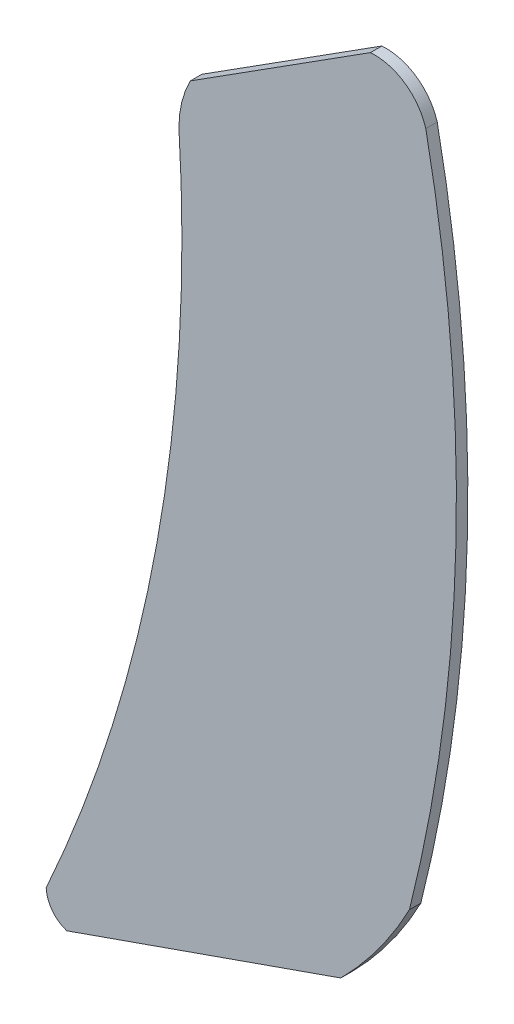
SolidWorks part; units mm, degrees
ref_plane "Спереди" through (0, 0, 0) normal (0, 0, 1) x (1, 0, 0)
ref_plane "Сверху" through (0, 0, 0) normal (0, 1, 0) x (1, 0, 0)
ref_plane "Справа" through (0, 0, 0) normal (1, 0, 0) x (0, 0, -1)
sketch "Эскиз1" plane through (0, 0, 0) normal (0, 0, 1) x (1, 0, 0)
  line L0 (79.6816, 239.4253) -> (32.4296, 209.3712)
  line L1 (71.9106, 25.2302) -> (0, 0)
  arc A0 (79.6816, 239.4253) -> (94.2106, 229.4253) centre (80.7814, 225.4686) cw
  arc A1 (94.2106, 229.4253) -> (89.9106, 49.7302) centre (-303.5993, 149.0457) cw
  arc A2 (89.9106, 49.7302) -> (71.9106, 25.2302) centre (-0.381, 97.2047) cw
  arc A3 (0, 0) -> (-5.4, 7.1) centre (2.349, 7.3901) cw
  arc A4 (32.4296, 209.3712) -> (29.4296, 197.1712) centre (55.3947, 197.2552) ccw
  arc A5 (29.4296, 197.1712) -> (-5.4, 7.1) centre (-369.7838, 172.0983) cw
  arc A6 (32.4296, 209.3712) -> (-3.3, 2.0778) centre (-302.3977, 160.357) cw
  arc A7 (79.6816, 239.4253) -> (71.9106, 25.2302) centre (-332.2163, 147.1305) cw
  point P17 (0, 0)
  point P18 (0, 0)
  point P19 (0, 0)
  point P20 (0, 0)
  point P21 (0, 0)
  point P22 (0, 0)
  point P23 (0, 0)
  point P24 (0, 0)
  dimension "D2" = 14
  dimension "D3" = 405.8492
  dimension "D4" = 400
  dimension "D5" = 7.7544
  dimension "D14" = 5.4
  dimension "D17" = 25.9652
  dimension "D1" = 56
  dimension "D6" = 71.9106
  dimension "D7" = 25.2302
  dimension "D8" = 214.1951
  dimension "D9" = 14.529
  dimension "D10" = 3
  dimension "D11" = 18
  dimension "D12" = 24.5
  dimension "D13" = 7.1
  dimension "D15" = 4.3
  dimension "D16" = 49.7302
  dimension "D18" = 12.2
  dimension "D19" = 47.252
  dimension "D20" = 64.781
  dimension "D21" = 10
  dimension "D22" = 3.3
  dimension "D23" = 2.0778
  dimension "D24" = 5.0222
  dimension "D25" = 2.1
extrude "Бобышка-Вытянуть1" add sketch "Эскиз1" along normal blind 3 contours A7 L0 A6 A3 L1 | A6 A4 A5 A3 | A0 A7 A2 A1
